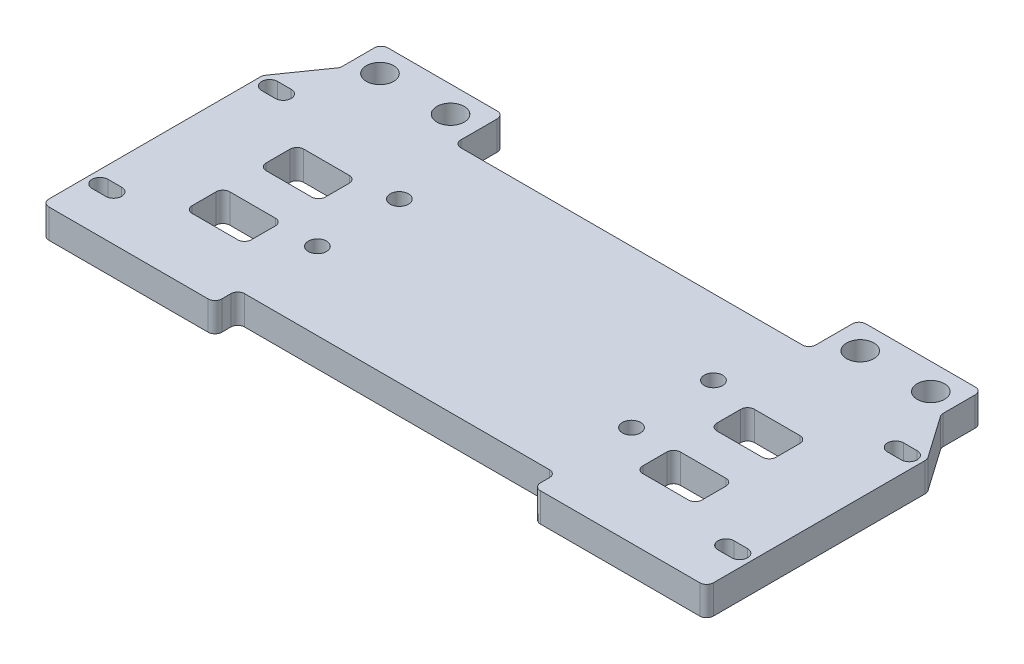
SolidWorks part; units mm, degrees
material "1060 Alloy"
ref_plane "Front Plane" through (0, 0, 0) normal (0, 0, 1) x (1, 0, 0)
ref_plane "Top Plane" through (0, 0, 0) normal (0, 1, 0) x (1, 0, 0)
ref_plane "Right Plane" through (0, 0, 0) normal (1, 0, 0) x (0, 0, -1)
sketch "Sketch1" plane through (0, 0, 0) normal (0, 1, 0) x (1, 0, 0)
  line L0 (38, 0) -> (38, 5)
  line L1 (0, 0) -> (38, 0)
  line L2 (0, 0) -> (0, 48.5)
  line L3 (7, 67.5) -> (34, 67.5)
  line L4 (96, 0) -> (96, 48.5)
  line L5 (0, 48.5) -> (7, 58.5)
  line L6 (7, 58.5) -> (7, 67.5)
  line L7 (34, 67.5) -> (34, 56.5)
  line L8 (48, -139.8616) -> (48, 139.8616) construction
  line L9 (58, 0) -> (58, 5)
  line L10 (96, 48.5) -> (89, 58.5)
  line L11 (89, 58.5) -> (89, 67.5)
  line L12 (62, 67.5) -> (62, 56.5)
  line L13 (38, 5) -> (58, 5)
  line L14 (58, 0) -> (96, 0)
  line L15 (34, 56.5) -> (62, 56.5)
  line L16 (62, 67.5) -> (89, 67.5)
  line L17 (79, 14.5) -> (66, 14.5)
  line L18 (17, 39) -> (30, 39)
  line L19 (17, 39) -> (17, 30.75)
  line L20 (17, 30.75) -> (30, 30.75)
  line L21 (30, 39) -> (30, 30.75)
  line L22 (17, 22.75) -> (30, 22.75)
  line L23 (17, 22.75) -> (17, 14.5)
  line L24 (17, 14.5) -> (30, 14.5)
  line L25 (30, 22.75) -> (30, 14.5)
  line L26 (66, 22.75) -> (66, 14.5)
  line L27 (79, 22.75) -> (66, 22.75)
  line L28 (79, 22.75) -> (79, 14.5)
  line L29 (79, 30.75) -> (66, 30.75)
  line L30 (66, 39) -> (66, 30.75)
  line L31 (79, 39) -> (66, 39)
  line L32 (79, 39) -> (79, 30.75)
  line L33 (2.75, 11.75) -> (5.75, 11.75)
  line L34 (2.75, 8.25) -> (5.75, 8.25)
  line L35 (93.25, 8.25) -> (90.25, 8.25)
  line L36 (93.25, 11.75) -> (90.25, 11.75)
  line L37 (-107.8769, 28.625) -> (107.8769, 28.625) construction
  line L38 (93.25, 45.5) -> (90.25, 45.5)
  line L39 (93.25, 49) -> (90.25, 49)
  line L40 (2.75, 49) -> (5.75, 49)
  line L41 (2.75, 45.5) -> (5.75, 45.5)
  circle A0 centre (38.5, 40) radius 2
  circle A1 centre (38.5, 22) radius 2
  circle A2 centre (57.5, 22) radius 2
  circle A3 centre (57.5, 40) radius 2
  arc A4 (2.75, 11.75) -> (2.75, 8.25) centre (2.75, 10) ccw
  arc A5 (5.75, 8.25) -> (5.75, 11.75) centre (5.75, 10) ccw
  arc A6 (93.25, 11.75) -> (93.25, 8.25) centre (93.25, 10) cw
  arc A7 (90.25, 8.25) -> (90.25, 11.75) centre (90.25, 10) cw
  arc A8 (93.25, 45.5) -> (93.25, 49) centre (93.25, 47.25) ccw
  arc A9 (90.25, 49) -> (90.25, 45.5) centre (90.25, 47.25) ccw
  arc A10 (2.75, 45.5) -> (2.75, 49) centre (2.75, 47.25) cw
  arc A11 (5.75, 49) -> (5.75, 45.5) centre (5.75, 47.25) cw
  circle A12 centre (12.5, 61.75) radius 3
  circle A13 centre (28, 61.75) radius 3
  circle A14 centre (68, 61.75) radius 3
  circle A15 centre (83.5, 61.75) radius 3
  point P14 (48, 0)
  point P59 (0, 28.625)
  dimension "D18" = 4
  dimension "D22" = 3.5
  dimension "D23" = 10
  dimension "D24" = 2.75
  dimension "D25" = 3.5
  dimension "D28" = 6
  dimension "D29" = 5.75
  dimension "D31" = 15.5
  dimension "D1" = 96
  dimension "D2" = 27
  dimension "D3" = 38
  dimension "D4" = 5
  dimension "D5" = 19
  dimension "D6" = 7
  dimension "D7" = 10
  dimension "D8" = 11
  dimension "D9" = 67.5
  dimension "D10" = 8.25
  dimension "D11" = 8.25
  dimension "D12" = 13
  dimension "D13" = 13
  dimension "D14" = 17
  dimension "D15" = 17
  dimension "D16" = 14.5
  dimension "D17" = 8
  dimension "D19" = 16.5
  dimension "D20" = 8.5
  dimension "D21" = 18
  dimension "D26" = 3
  dimension "D27" = 18.625
  dimension "D30" = 5.5
extrude "Boss-Extrude1" add sketch "Sketch1" along normal blind 6.35
fillet "Fillet1" radius 1.5 32 edges at (17, 3.175, -30.75) (17, 3.175, -14.5) (17, 3.175, -22.75) (17, 3.175, -39) (66, 3.175, -22.75) (66, 3.175, -39) (66, 3.175, -30.75) (66, 3.175, -14.5) (79, 3.175, -14.5) (79, 3.175, -30.75) (79, 3.175, -39) (79, 3.175, -22.75) (30, 3.175, -22.75) (30, 3.175, -14.5) (30, 3.175, -30.75) (30, 3.175, -39) (38, 3.175, -5) (58, 3.175, -5) (96, 3.175, -48.5) (89, 3.175, -58.5) (89, 3.175, -67.5) (62, 3.175, -67.5) (62, 3.175, -56.5) (34, 3.175, -56.5) (34, 3.175, -67.5) (7, 3.175, -67.5) (7, 3.175, -58.5) (0, 3.175, -48.5) (0, 3.175, 0) (96, 3.175, 0) (58, 3.175, 0) (38, 3.175, 0)
ref_plane "Plane1" through (48, 0, 0) normal (1, 0, 0) x (0, 0, -1)
sketch "Sketch2" plane through (48, 0, 0) normal (1, 0, 0) x (0, 0, -1)
  line L1 (-7.8701, 8.545) -> (74.4577, 8.545)
  line L2 (-7.8701, 8.545) -> (-7.8701, -5.9133)
  line L3 (-7.8701, -5.9133) -> (74.4577, -5.9133)
  line L4 (74.4577, 8.545) -> (74.4577, -5.9133)
extrude "Cut-Extrude1" cut sketch "Sketch2" along normal blind 51
sketch "Sketch3" plane through (48, 0, 0) normal (1, 0, 0) x (0, 0, -1)
  line L4 (5, 6.35) -> (5, 0)
  line L5 (5, 0) -> (56.5, 0)
  line L6 (56.5, 0) -> (56.5, 6.35)
  line L7 (56.5, 6.35) -> (5, 6.35)
  line L8 (5, 6.35) -> (5, 0)
  line L9 (5, 0) -> (56.5, 0)
  line L10 (56.5, 0) -> (56.5, 6.35)
  line L11 (56.5, 6.35) -> (5, 6.35)
  dimension "D1" = 0
extrude "Boss-Extrude2" add sketch "Sketch3" along normal blind 25
mirror "Mirror1" about plane through (73, 0, 0) normal (1, 0, 0) of bodies 103
